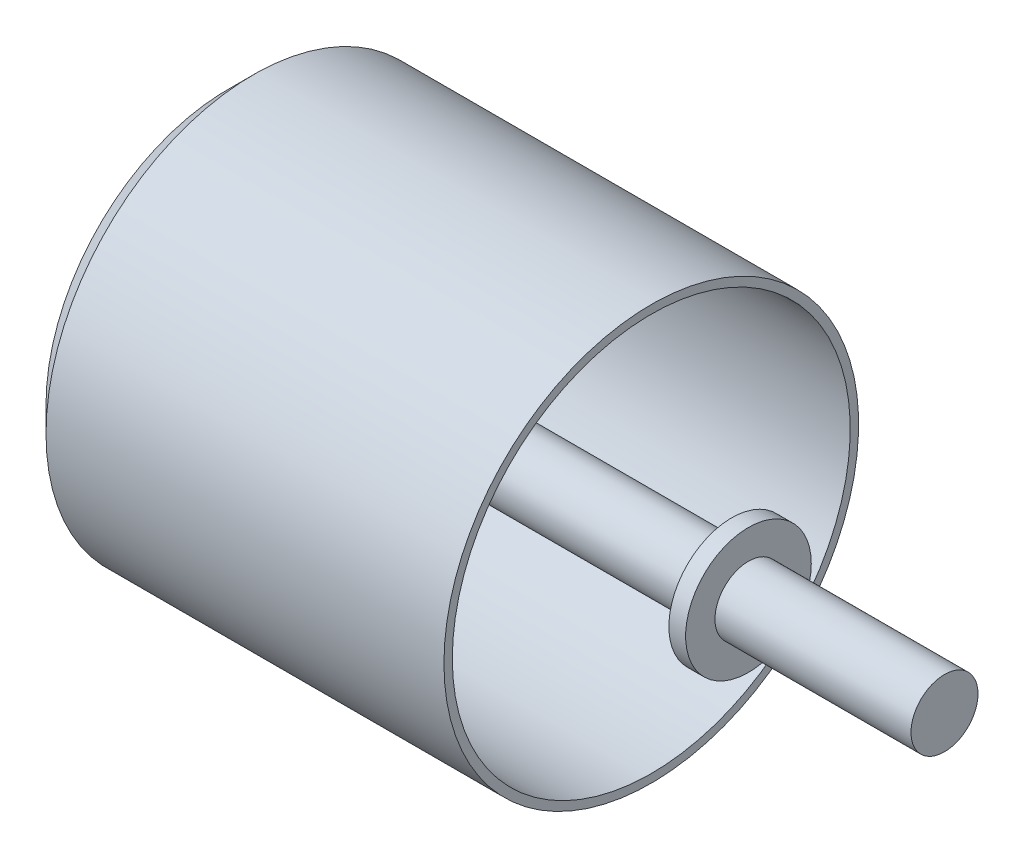
SolidWorks part; units mm, degrees
ref_plane "Front Plane" through (0, 0, 0) normal (0, 0, 1) x (1, 0, 0)
ref_plane "Top Plane" through (0, 0, 0) normal (0, 1, 0) x (1, 0, 0)
ref_plane "Right Plane" through (0, 0, 0) normal (1, 0, 0) x (0, 0, -1)
sketch "Sketch1" plane through (0, 0, 0) normal (0, 0, 1) x (1, 0, 0)
  line L0 (0, 0) -> (80.0956, 0) construction
  line L1 (0, 21.75) -> (3, 24.75)
  line L3 (0, 0) -> (0, 21.75)
  line L4 (0, 0) -> (1, 0)
  line L6 (1, 0) -> (1, 21.3358)
  line L7 (1, 21.3358) -> (3.4142, 23.75)
  line L8 (3.4142, 23.75) -> (50.5, 23.75)
  line L9 (50.5, 23.75) -> (50.5, 24.75)
  line L15 (3, 24.75) -> (50.5, 24.75)
  dimension "D1" = 135
  dimension "D2" = 1
  dimension "D3" = 1
  dimension "D4" = 49.5
  dimension "D5" = 50.5
  dimension "D6" = 47.5
revolve "Revolve1" add sketch "Sketch1" angle 360 about L0
sketch "Sketch2" plane through (0, 0, 0) normal (1, 0, 0) x (0, 0, -1)
  circle A0 centre (0, 0) radius 4
  dimension "D1" = 8
extrude "Boss-Extrude1" add sketch "Sketch2" along normal blind 85.5
sketch "Sketch3" plane through (0, 0, 0) normal (-1, 0, 0) x (0, 0, 1)
  line L0 (-17, 0) -> (17, 0) construction
  line L1 (0, 17) -> (0, -17) construction
  circle A0 centre (0, 17) radius 3.5
  circle A1 centre (17, 0) radius 3.5
  circle A2 centre (0, -17) radius 3.5
  circle A3 centre (-17, 0) radius 3.5
  circle A4 centre (0, 0) radius 17 construction
  dimension "D1" = 34
  dimension "D2" = 7
extrude "Cut-Extrude1" cut sketch "Sketch3" against normal through all
sketch "Sketch4" plane through (60.1, 0, 0) normal (1, 0, 0) x (0, 0, -1)
  circle A0 centre (0, 0) radius 7.5
  dimension "D1" = 15
extrude "Boss-Extrude2" add sketch "Sketch4" along normal blind 2
